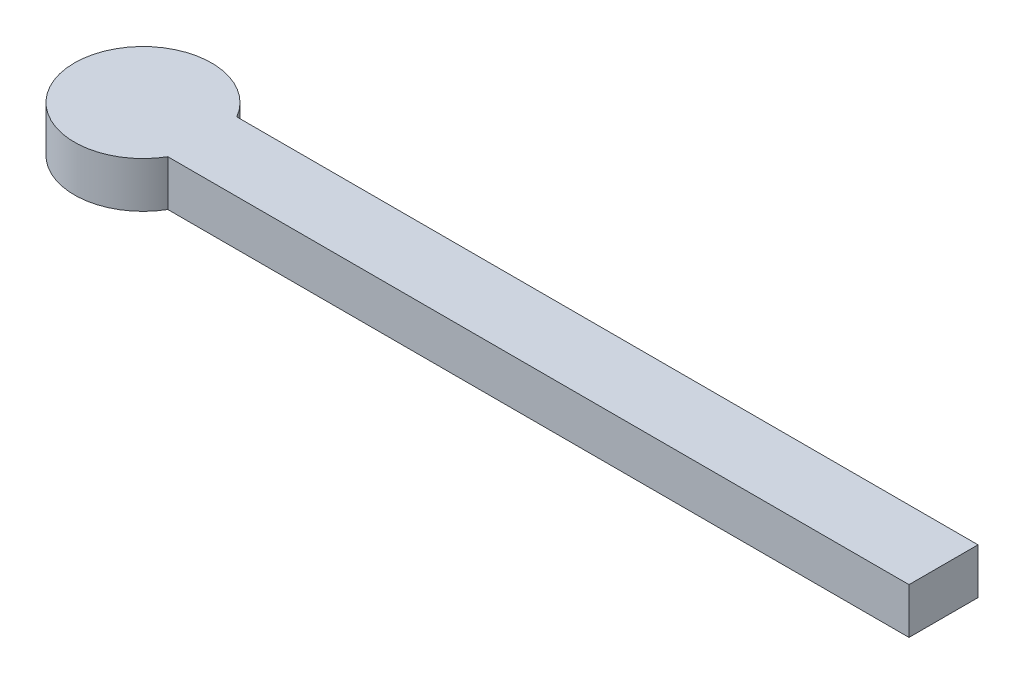
SolidWorks part; units mm, degrees
ref_plane "Plan de face" through (0, 0, 0) normal (0, 0, 1) x (1, 0, 0)
ref_plane "Plan de dessus" through (0, 0, 0) normal (0, 1, 0) x (1, 0, 0)
ref_plane "Plan de droite" through (0, 0, 0) normal (1, 0, 0) x (0, 0, -1)
sketch "Sketch1" plane through (0, 0, 0) normal (0, 1, 0) x (1, 0, 0)
  line L1 (174.9579, -7.5393) -> (12.9676, -7.5393)
  line L2 (174.9579, -7.5393) -> (174.9579, 7.5393)
  line L3 (174.9579, 7.5393) -> (12.9676, 7.5393)
  line L5 (174.9579, -7.5393) -> (12.9676, 7.5393) construction
  line L6 (174.9579, 7.5393) -> (12.9676, -7.5393) construction
  arc A0 (12.9676, 7.5393) -> (12.9676, -7.5393) centre (0, 0) ccw
  point P3 (93.9628, 0)
  point P8 (0, 0)
  dimension "D1" = 15
extrude "Boss-Extrude1" add sketch "Sketch1" along normal blind 10
